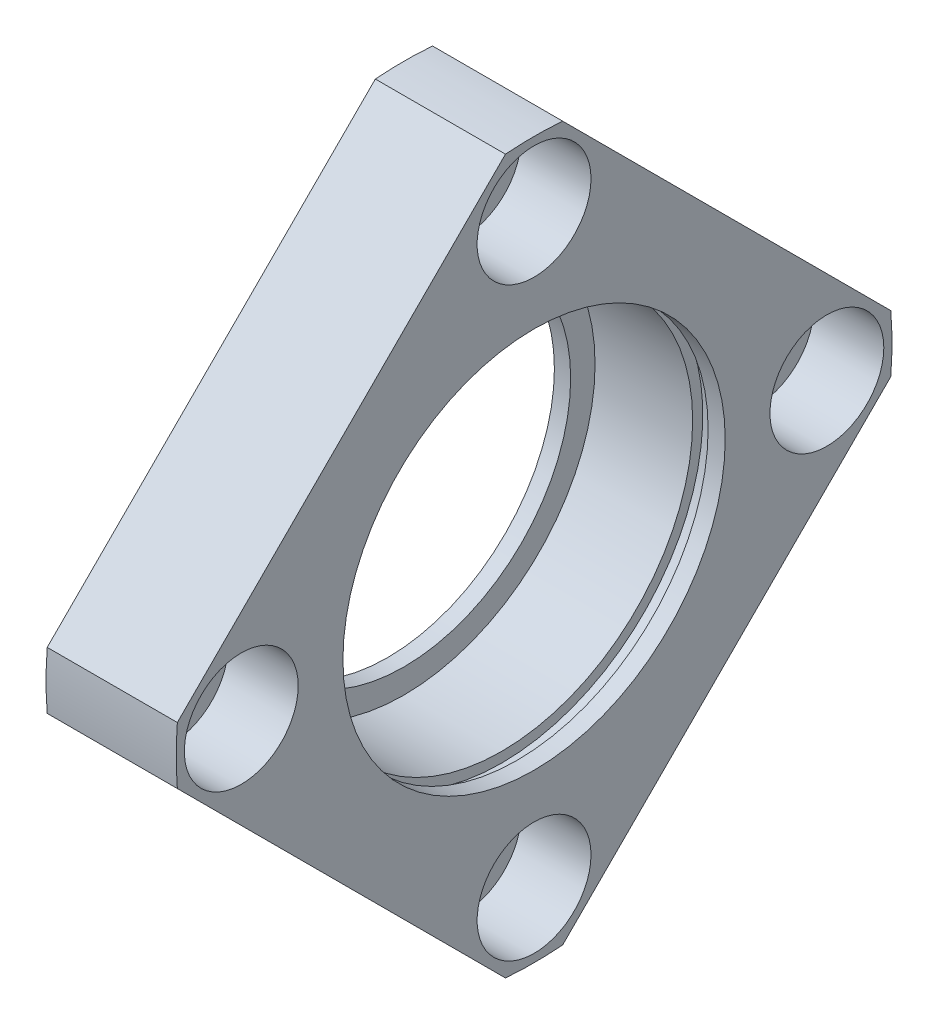
SolidWorks part; units mm, degrees
ref_plane "Front Plane" through (0, 0, 0) normal (0, 0, 1) x (1, 0, 0)
ref_plane "Top Plane" through (0, 0, 0) normal (0, 1, 0) x (1, 0, 0)
ref_plane "Right Plane" through (0, 0, 0) normal (1, 0, 0) x (0, 0, -1)
sketch "Sketch1" plane through (0, 0, 0) normal (0, 0, 1) x (1, 0, 0)
  line L0 (0, 0) -> (-18, 0) construction
  line L1 (0, 44) -> (-16, 44)
  line L2 (-16, 44) -> (-16, 27)
  line L3 (-16, 27) -> (-18, 27)
  line L4 (-18, 27) -> (-18, 20.5)
  line L5 (-18, 20.5) -> (-16, 20.5)
  line L6 (-16, 20.5) -> (-16, 23.5)
  line L7 (-16, 23.5) -> (-4, 23.5)
  line L8 (-4, 23.5) -> (-4, 24.75)
  line L9 (-4, 24.75) -> (-2.1, 24.75)
  line L10 (-2.1, 24.75) -> (-2.1, 23.5)
  line L11 (-2.1, 23.5) -> (0, 23.5)
  line L12 (0, 23.5) -> (0, 44)
  line L13 (0, 12.5) -> (-18, 12.5) construction
  dimension "H" = 88
  dimension "DH_s" = 41
  dimension "D" = 47
  dimension "MSM_1" = 49.5
  dimension "T1" = 16
  dimension "S" = 2
  dimension "D1." = 54
  dimension "L1_s" = 2
  dimension "B" = 12
  dimension "MSM_2" = 1.9
  dimension "T" = 18
  dimension "D_s" = 25
revolve "Revolve1" add sketch "Sketch1" angle 360 about L0
fillet "Fillet1" radius 0.3 1 edges at (-16, 27, 0)
hole_wizard "Diameter Hole1" positions "Sketch3" profile "Sketch2" hole size "Ø8.0" standard "JIS"
sketch "Sketch3" plane through (0, 0, 0) normal (1, 0, 0) x (0, 0, -1)
  circle A0 centre (0, 0) radius 36 construction
  point P0 (0, 36)
  point P9 (-36, 0)
  point P11 (36, 0)
  point P13 (0, -36)
  dimension "P.C.D." = 72
sketch "Sketch2" plane through (0, 36, 0) normal (0, 1, 0) x (0, 0, -1)
  line L0 (0, 0) -> (0, 8.6)
  line L1 (0, 8.6) -> (7, 8.6)
  line L2 (7, 8.6) -> (7, 0)
  line L5 (7, 0) -> (0, 0)
  line L10 (0, 8.6) -> (-7, 8.6) construction
  line L11 (0, 0) -> (0, 8.6) construction
  dimension "D1_s" = 14
  dimension "H1" = 8.6
  dimension "Drill Angle" = 180
hole_wizard "Tapped Hole1" positions "Sketch5" profile "Sketch4" tap size "M10x1.5" standard "JIS" end condition through all
sketch "Sketch5" plane through (-8.6, 0, 0) normal (1, 0, 0) x (0, 0, -1)
  point P0 (0, 36)
  point P3 (-36, 0)
  point P6 (0, -36)
  point P9 (36, 0)
sketch "Sketch4" plane through (-8.6, 36, 0) normal (0, 1, 0) x (0, 0, -1)
  line L0 (0, 0) -> (0, 9.4)
  line L1 (0, 9.4) -> (4.25, 9.4)
  line L2 (4.25, 9.4) -> (4.25, 0)
  line L5 (4.25, 0) -> (0, 0)
  line L11 (0, 0) -> (0, 9.4) construction
  dimension "Thru Tap Drill Dia." = 8.5
  dimension "Thru Tap Drill Depth" = 9.4
cosmetic thread "Hole Thread1" parameters "M"=10
cosmetic thread "Hole Thread2" parameters "M"=10
cosmetic thread "Hole Thread3" parameters "M"=10
cosmetic thread "Hole Thread4" parameters "M"=10
sketch "Sketch6" plane through (-16, 0, 0) normal (1, 0, 0) x (0, 0, -1)
  line L0 (-43.8592, 3.5169) -> (-3.5169, 43.8592)
  line L1 (0, 44) -> (0, 0) construction
  line L2 (3.5169, 43.8592) -> (43.8592, 3.5169)
  line L3 (43.8592, -3.5169) -> (3.5169, -43.8592)
  line L4 (-3.5169, -43.8592) -> (-43.8592, -3.5169)
  circle A0 centre (0, 0) radius 33.5 construction
  circle A1 centre (0, 0) radius 44 construction
  arc A2 (-3.5169, 43.8592) -> (-43.8592, 3.5169) centre (0, 0) ccw
  arc A3 (-43.8592, -3.5169) -> (-3.5169, -43.8592) centre (0, 0) ccw
  arc A4 (3.5169, -43.8592) -> (43.8592, -3.5169) centre (0, 0) ccw
  arc A5 (43.8592, 3.5169) -> (3.5169, 43.8592) centre (0, 0) ccw
  dimension "K" = 67
extrude "Cut-Extrude1" cut sketch "Sketch6" along normal through all
other "DeleteFace1" [suppressed]
sketch "Sketch7" [suppressed] plane through (-9, 0, 0) normal (1, 0, 0) x (0, 0, -1)
  line L0 (-12.5, 16.2481) -> (-12.5, -16.2481)
  line L1 (12.5, 16.2481) -> (12.5, -16.2481)
  arc A0 (12.5, -16.2481) -> (12.5, 16.2481) centre (0, 0) ccw
  circle A1 centre (0, 0) radius 20.5 construction
  arc A2 (-12.5, 16.2481) -> (-12.5, -16.2481) centre (0, 0) ccw
  dimension "W" = 25
extrude "Cut-Extrude2" [suppressed] cut sketch "Sketch7" along normal through all
hole_wizard "Diameter Hole2" [suppressed] positions "Sketch9" profile "Sketch8" hole size "Ø6.5" standard "JIS"
sketch "Sketch9" [suppressed] plane through (0, 0, 0) normal (1, 0, 0) x (0, 0, -1)
  line L2 (0, 15.5) -> (0, -15.5) construction
  point P0 (0, -15.5)
  point P2 (0, 15.5)
  dimension "A" = 31
sketch "Sketch8" [suppressed] plane through (0, -15.5, 0) normal (0, 1, 0) x (0, 0, -1)
  line L0 (0, 0) -> (0, 4.4)
  line L1 (0, 4.4) -> (4, 4.4)
  line L2 (4, 4.4) -> (4, 0)
  line L5 (4, 0) -> (0, 0)
  line L10 (0, 4.4) -> (-4, 4.4) construction
  line L11 (0, 0) -> (0, 4.4) construction
  dimension "D1_s" = 14
  dimension "H1" = 8.6
  dimension "Drill Angle" = 180
hole_wizard "Tapped Hole2" [suppressed] positions "Sketch11" profile "Sketch10" tap size "M5x0.8" standard "JIS"
sketch "Sketch11" [suppressed] plane through (-4.4, 0, 0) normal (1, 0, 0) x (0, 0, -1)
  point P0 (0, 15.5)
  point P3 (0, -15.5)
sketch "Sketch10" [suppressed] plane through (-4.4, 15.5, 0) normal (0, 1, 0) x (0, 0, -1)
  line L0 (0, 0) -> (0, 6.6)
  line L1 (0, 6.6) -> (2.1, 6.6)
  line L2 (2.1, 6.6) -> (2.1, 0)
  line L5 (2.1, 0) -> (0, 0)
  line L11 (0, 0) -> (0, 6.6) construction
  dimension "Thru Tap Drill Dia." = 4.2
  dimension "Thru Tap Drill Depth" = 6.6
cosmetic thread "Hole Thread5" [suppressed] parameters "M"=5
cosmetic thread "Hole Thread6" [suppressed] parameters "M"=5
hole_wizard "Diameter Hole3" [suppressed] positions "Sketch13" profile "Sketch12" hole size "Ø6.5" standard "JIS"
sketch "Sketch13" [suppressed] plane through (0, 0, 0) normal (1, 0, 0) x (0, 0, -1)
  line L1 (0, 0) -> (20, 0) construction
  line L2 (20, 22.3607) -> (20, -22.3607) construction
  line L3 (0, 0) -> (0, -30) construction
  arc A1 (-20, -22.3607) -> (20, -22.3607) centre (0, 0) ccw construction
  point P0 (14.5, 15.5)
  point P2 (-14.5, 15.5)
  point P4 (-14.5, -15.5)
  point P6 (14.5, -15.5)
  dimension "F" = 29
  dimension "A" = 31
sketch "Sketch12" [suppressed] plane through (0, 15.5, -14.5) normal (0, 1, 0) x (0, 0, -1)
  line L0 (0, 0) -> (0, 4.4)
  line L1 (0, 4.4) -> (4, 4.4)
  line L2 (4, 4.4) -> (4, 0)
  line L5 (4, 0) -> (0, 0)
  line L10 (0, 4.4) -> (-4, 4.4) construction
  line L11 (0, 0) -> (0, 4.4) construction
  dimension "D1_s" = 14
  dimension "H1" = 8.6
  dimension "Drill Angle" = 180
hole_wizard "Tapped Hole3" [suppressed] positions "Sketch15" profile "Sketch14" tap size "M5x0.8" standard "JIS"
sketch "Sketch15" [suppressed] plane through (-4.4, 0, 0) normal (1, 0, 0) x (0, 0, -1)
  point P0 (-14.5, 15.5)
  point P2 (14.5, 15.5)
  point P5 (14.5, -15.5)
  point P8 (-14.5, -15.5)
sketch "Sketch14" [suppressed] plane through (-4.4, 15.5, 14.5) normal (0, 1, 0) x (0, 0, -1)
  line L0 (0, 0) -> (0, 6.6)
  line L1 (0, 6.6) -> (2.1, 6.6)
  line L2 (2.1, 6.6) -> (2.1, 0)
  line L5 (2.1, 0) -> (0, 0)
  line L11 (0, 0) -> (0, 6.6) construction
  dimension "Thru Tap Drill Dia." = 4.2
  dimension "Thru Tap Drill Depth" = 6.6
cosmetic thread "Hole Thread7" [suppressed] parameters "M"=5
cosmetic thread "Hole Thread8" [suppressed] parameters "M"=5
cosmetic thread "Hole Thread9" [suppressed] parameters "M"=5
cosmetic thread "Hole Thread10" [suppressed] parameters "M"=5
